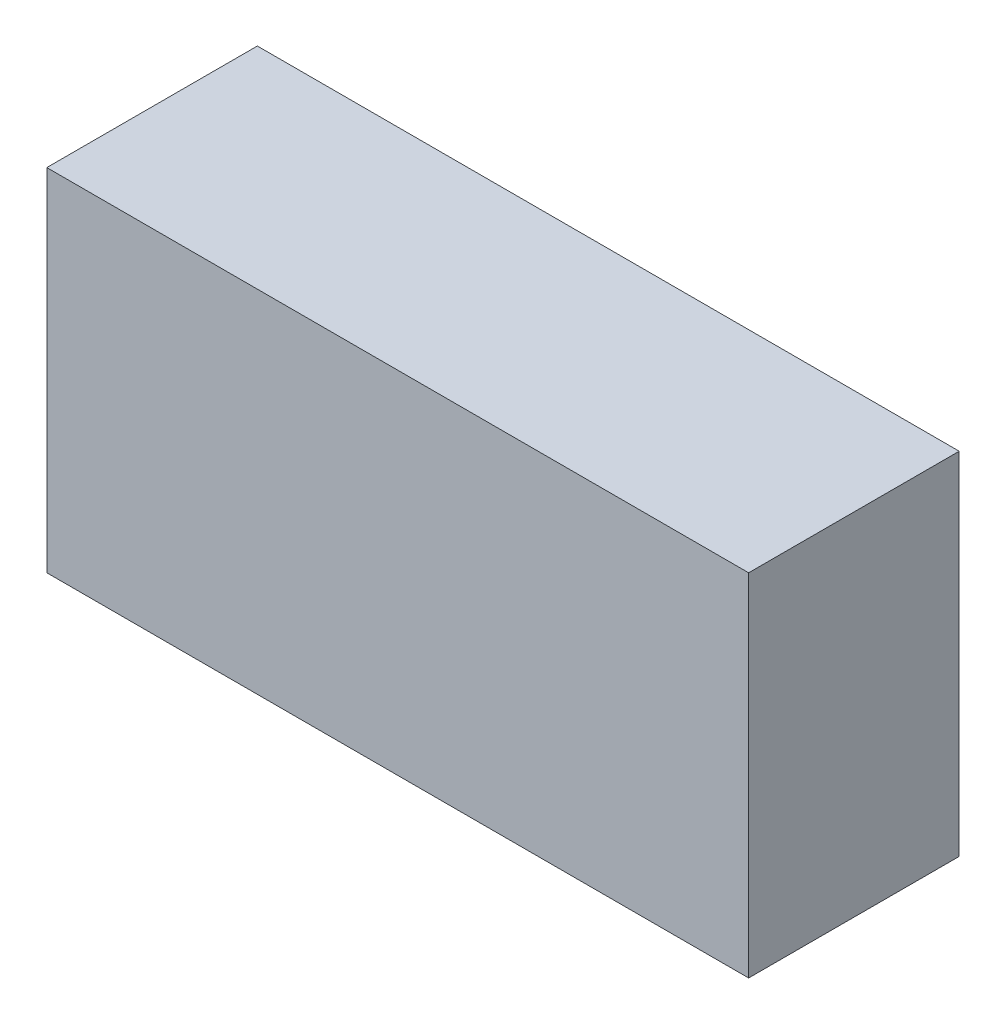
SolidWorks part; units mm, degrees
ref_plane "Front Plane" through (0, 0, 0) normal (0, 0, 1) x (1, 0, 0)
ref_plane "Top Plane" through (0, 0, 0) normal (0, 1, 0) x (1, 0, 0)
ref_plane "Right Plane" through (0, 0, 0) normal (1, 0, 0) x (0, 0, -1)
sketch "Sketch1" plane through (0, 0, 0) normal (0, 0, 1) x (1, 0, 0)
  line L1 (0, 0) -> (10, 0)
  line L2 (0, 0) -> (0, 5)
  line L3 (0, 5) -> (10, 5)
  line L4 (10, 0) -> (10, 5)
  dimension "D1" = 10
  dimension "D2" = 5
extrude "Boss-Extrude1" add sketch "Sketch1" along normal blind 3
